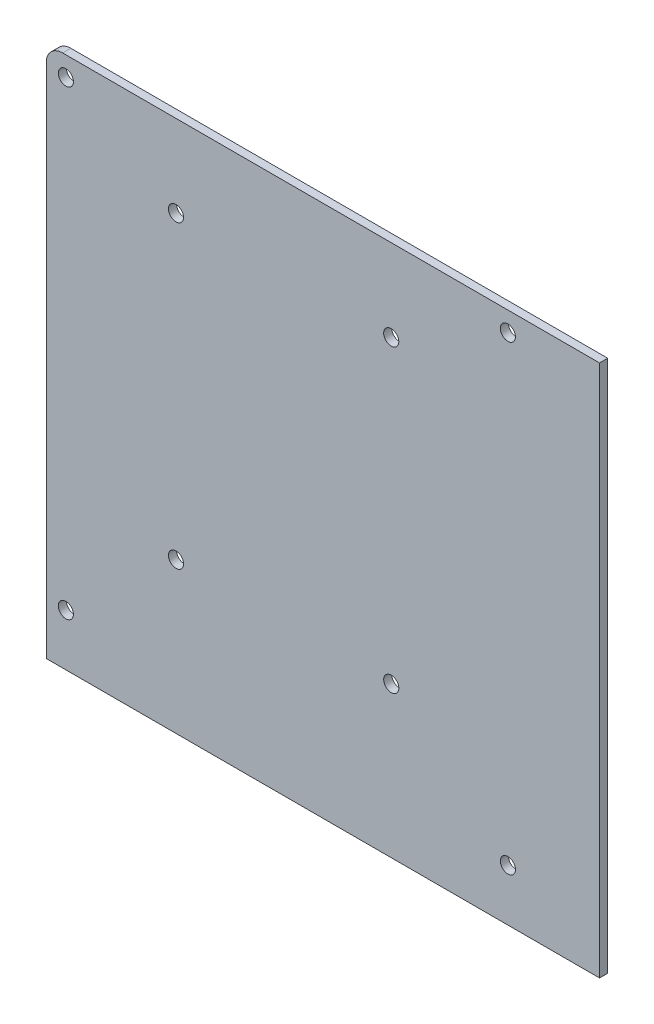
SolidWorks part; units mm, degrees
ref_plane "Front Plane" through (0, 0, 0) normal (0, 0, 1) x (1, 0, 0)
ref_plane "Top Plane" through (0, 0, 0) normal (0, 1, 0) x (1, 0, 0)
ref_plane "Right Plane" through (0, 0, 0) normal (1, 0, 0) x (0, 0, -1)
sketch "Sketch1" plane through (0, 0, 0) normal (0, 0, 1) x (1, 0, 0)
  line L1 (0, 0) -> (254, 0)
  line L2 (0, 0) -> (0, 381)
  line L3 (0, 381) -> (254, 381)
  line L4 (254, 0) -> (254, 381)
  dimension "D1" = 381
  dimension "D2" = 254
extrude "Boss-Extrude1" add sketch "Sketch1" along normal blind 1.5875
sketch "Sketch2" plane through (0, 0, 1.5875) normal (0, 0, 1) x (1, 0, 0)
  line L0 (89.8652, 377.19) -> (89.8652, 3.81) construction
  line L1 (0, 381) -> (254, 381) construction
  line L2 (127, 381) -> (127, 377.19) construction
  line L3 (3.81, 377.19) -> (250.19, 377.19) construction
  line L5 (164.1348, 377.19) -> (164.1348, 3.81) construction
  line L6 (3.81, 377.19) -> (3.81, 3.81) construction
  line L7 (3.81, 3.81) -> (250.19, 3.81) construction
  line L8 (250.19, 3.81) -> (250.19, 377.19) construction
  line L9 (3.81, 190.5) -> (250.19, 190.5) construction
  line L10 (3.81, 287.3756) -> (250.19, 287.3756) construction
  line L11 (3.81, 93.6244) -> (250.19, 93.6244) construction
  line L12 (0, 381) -> (0, 0) construction
  line L13 (0, 190.5) -> (3.81, 190.5) construction
  circle A0 centre (3.81, 377.19) radius 1.4732
  circle A1 centre (89.8652, 377.19) radius 1.4732
  circle A2 centre (164.1348, 377.19) radius 1.4732
  circle A3 centre (250.19, 377.19) radius 1.4732
  circle A4 centre (164.1348, 287.3755) radius 1.4732
  circle A5 centre (3.81, 287.3756) radius 1.4732
  circle A6 centre (250.19, 287.3756) radius 1.4732
  circle A7 centre (89.8652, 287.3756) radius 1.4732
  circle A8 centre (164.1348, 190.5) radius 1.4732
  circle A9 centre (3.81, 191.135) radius 1.4732
  circle A10 centre (250.19, 190.5) radius 1.4732
  circle A11 centre (89.8652, 190.5) radius 1.4732
  circle A12 centre (164.1348, 93.6244) radius 1.4732
  circle A13 centre (3.81, 93.6244) radius 1.4732
  circle A14 centre (250.19, 93.6244) radius 1.4732
  circle A15 centre (89.8652, 93.6244) radius 1.4732
  circle A16 centre (164.1348, 3.81) radius 1.4732
  circle A17 centre (3.81, 3.81) radius 1.4732
  circle A18 centre (250.19, 3.81) radius 1.4732
  circle A19 centre (89.8652, 3.81) radius 1.4732
  dimension "D6" = 2.9464
  dimension "D23" = 0
  dimension "D24" = 0
  dimension "D25" = 0
  dimension "D28" = 0
  dimension "D29" = 0
  dimension "D30" = 0
  dimension "D31" = 0
  dimension "D32" = 86.0552
  dimension "D1" = 246.38
  dimension "D3" = 373.38
  dimension "D4" = 96.8756
  dimension "D5" = 96.8756
  dimension "D7" = 86.0552
  dimension "D8" = 86.0552
  dimension "D9" = 0
  dimension "D10" = 0
  dimension "D11" = 0
  dimension "D12" = 86.0552
  dimension "D13" = 0
  dimension "D14" = 0
  dimension "D15" = 0
  dimension "D16" = 0
  dimension "D17" = 0
  dimension "D18" = 0
  dimension "D19" = 0
  dimension "D20" = 0
  dimension "D21" = 0
  dimension "D22" = 0
  dimension "D26" = 0
  dimension "D27" = 0
extrude "Cut-Extrude1" cut sketch "Sketch2" against normal through all contours A0 | A2 | A3
fillet "Fillet1" radius 3.175 4 edges at (254, 0, 0.7937) (0, 0, 0.7937) (254, 381, 0.7937) (0, 381, 0.7937)
sketch "Sketch3" plane through (0, 0, 1.5875) normal (0, 0, 1) x (1, 0, 0)
  line L0 (9.9695, 45.1866) -> (46.2026, 45.1866) construction
  line L1 (46.2026, 45.1866) -> (46.2026, 9.9695) construction
  line L2 (81.2038, 28.3591) -> (82.4357, 28.3591) construction
  line L3 (82.4357, 29.591) -> (82.4357, 60.7822)
  line L4 (73.0377, 11.2014) -> (73.0377, 20.193)
  line L5 (81.2038, 62.0141) -> (82.4357, 62.0141) construction
  line L6 (71.8058, 9.9695) -> (20.5994, 9.9695)
  line L7 (19.3675, 11.2014) -> (19.3675, 20.193)
  line L8 (11.2014, 28.3591) -> (9.9695, 28.3591) construction
  line L9 (9.9695, 29.591) -> (9.9695, 60.7822)
  line L10 (73.0377, 79.1718) -> (73.0377, 70.1802)
  line L11 (71.8058, 80.4037) -> (20.5994, 80.4037)
  line L12 (3.175, 0) -> (250.825, 0) construction
  line L13 (0, 377.825) -> (0, 3.175) construction
  line L14 (11.2014, 62.0141) -> (9.9695, 62.0141) construction
  line L15 (19.3675, 79.1718) -> (19.3675, 70.1802)
  line L16 (17.78, 79.1718) -> (17.78, 70.1802)
  line L17 (8.382, 29.591) -> (8.382, 60.7822)
  line L18 (17.78, 11.2014) -> (17.78, 20.193)
  line L19 (71.8058, 8.382) -> (20.5994, 8.382)
  line L20 (74.6252, 11.2014) -> (74.6252, 20.193)
  line L21 (84.0232, 29.591) -> (84.0232, 60.7822)
  line L22 (74.6252, 79.1718) -> (74.6252, 70.1802)
  line L23 (71.8058, 81.9912) -> (20.5994, 81.9912)
  arc A0 (19.3675, 20.193) -> (11.2014, 28.3591) centre (11.2014, 20.193) ccw
  arc A1 (9.9695, 29.591) -> (11.2014, 28.3591) centre (11.2014, 29.591) ccw
  arc A2 (19.3675, 11.2014) -> (20.5994, 9.9695) centre (20.5994, 11.2014) ccw
  arc A3 (73.0377, 11.2014) -> (71.8058, 9.9695) centre (71.8058, 11.2014) cw
  arc A4 (82.4357, 29.591) -> (81.2038, 28.3591) centre (81.2038, 29.591) cw
  arc A5 (73.0377, 20.193) -> (81.2038, 28.3591) centre (81.2038, 20.193) cw
  arc A6 (73.0377, 70.1802) -> (81.2038, 62.0141) centre (81.2038, 70.1802) ccw
  arc A7 (82.4357, 60.7822) -> (81.2038, 62.0141) centre (81.2038, 60.7822) ccw
  arc A8 (73.0377, 79.1718) -> (71.8058, 80.4037) centre (71.8058, 79.1718) ccw
  arc A9 (19.3675, 79.1718) -> (20.5994, 80.4037) centre (20.5994, 79.1718) cw
  arc A10 (9.9695, 60.7822) -> (11.2014, 62.0141) centre (11.2014, 60.7822) cw
  arc A11 (19.3675, 70.1802) -> (11.2014, 62.0141) centre (11.2014, 70.1802) cw
  arc A12 (17.78, 70.1802) -> (11.2014, 63.6016) centre (11.2014, 70.1802) cw
  arc A13 (8.382, 60.7822) -> (11.2014, 63.6016) centre (11.2014, 60.7822) cw
  arc A14 (8.382, 29.591) -> (11.2014, 26.7716) centre (11.2014, 29.591) ccw
  arc A15 (17.78, 20.193) -> (11.2014, 26.7716) centre (11.2014, 20.193) ccw
  arc A16 (17.78, 11.2014) -> (20.5994, 8.382) centre (20.5994, 11.2014) ccw
  arc A17 (74.6252, 11.2014) -> (71.8058, 8.382) centre (71.8058, 11.2014) cw
  arc A18 (74.6252, 20.193) -> (81.2038, 26.7716) centre (81.2038, 20.193) cw
  arc A19 (84.0232, 29.591) -> (81.2038, 26.7716) centre (81.2038, 29.591) cw
  arc A20 (84.0232, 60.7822) -> (81.2038, 63.6016) centre (81.2038, 60.7822) ccw
  arc A21 (74.6252, 70.1802) -> (81.2038, 63.6016) centre (81.2038, 70.1802) ccw
  arc A22 (74.6252, 79.1718) -> (71.8058, 81.9912) centre (71.8058, 79.1718) ccw
  arc A23 (17.78, 79.1718) -> (20.5994, 81.9912) centre (20.5994, 79.1718) cw
  point P35 (82.4357, 45.1866)
  dimension "D6" = 8.1661
  dimension "D7" = 2.4638
  dimension "D8" = 1.2319
  dimension "D1" = 9.9695
  dimension "D2" = 9.9695
  dimension "D3" = 19.3675
  dimension "D4" = 28.3591
  dimension "D5" = 45.1866
  dimension "D10" = 46.2026
  dimension "D9" = 1.5875
sketch "Sketch4" plane through (0, 0, 1.5875) normal (0, 0, 1) x (1, 0, 0)
  line L0 (8.382, 60.7822) -> (8.382, 77.2287)
  line L1 (13.1445, 81.9912) -> (20.5994, 81.9912)
  line L2 (20.5994, 81.9912) -> (79.2607, 81.9912)
  line L3 (84.0232, 77.2287) -> (84.0232, 13.1445)
  line L4 (79.2607, 8.382) -> (13.1445, 8.382)
  line L5 (8.382, 13.1445) -> (8.382, 60.7822)
  line L6 (6.477, 60.7822) -> (6.477, 77.2287)
  line L7 (13.1445, 83.8962) -> (20.5994, 83.8962)
  line L8 (20.5994, 83.8962) -> (79.2607, 83.8962)
  line L9 (85.9282, 77.2287) -> (85.9282, 13.1445)
  line L10 (79.2607, 6.477) -> (13.1445, 6.477)
  line L11 (6.477, 13.1445) -> (6.477, 60.7822)
  arc A0 (13.1445, 81.9912) -> (8.382, 77.2287) centre (13.1445, 77.2287) ccw
  arc A1 (79.2607, 81.9912) -> (84.0232, 77.2287) centre (79.2607, 77.2287) cw
  arc A2 (84.0232, 13.1445) -> (79.2607, 8.382) centre (79.2607, 13.1445) cw
  arc A3 (8.382, 13.1445) -> (13.1445, 8.382) centre (13.1445, 13.1445) ccw
  arc A4 (13.1445, 83.8962) -> (6.477, 77.2287) centre (13.1445, 77.2287) ccw
  arc A5 (79.2607, 83.8962) -> (85.9282, 77.2287) centre (79.2607, 77.2287) cw
  arc A6 (85.9282, 13.1445) -> (79.2607, 6.477) centre (79.2607, 13.1445) cw
  arc A7 (6.477, 13.1445) -> (13.1445, 6.477) centre (13.1445, 13.1445) ccw
  dimension "D1" = 4.7625
  dimension "D2" = 1.905
sketch "Sketch5" plane through (0, 0, 1.5875) normal (0, 0, 1) x (1, 0, 0)
  line L0 (9.9695, 45.1866) -> (82.4357, 45.1866) construction
  line L1 (9.9695, 60.7822) -> (9.9695, 29.591) construction
  line L2 (82.4357, 29.591) -> (82.4357, 60.7822) construction
  line L3 (82.4357, 45.1866) -> (46.2026, 45.1866) construction
  line L4 (46.2026, 45.1866) -> (46.2026, 80.4037) construction
  line L5 (71.8058, 80.4037) -> (20.5994, 80.4037) construction
  circle A0 centre (25.2476, 74.3966) radius 1.4732
  circle A1 centre (67.1576, 74.3966) radius 1.4732
  circle A2 centre (67.1576, 15.9766) radius 1.4732
  circle A3 centre (25.2476, 15.9766) radius 1.4732
  dimension "D1" = 2.9464
  dimension "D2" = 20.955
  dimension "D3" = 29.21
extrude "Cut-Extrude3" cut sketch "Sketch5" against normal through all
pattern_linear "LPattern1" count 4 spacing 96.8756 along (0, 1, 0) count 2 spacing 161.5948 along (1, 0, 0) of "Cut-Extrude3"
sketch "Sketch6" plane through (0, 0, 1.5875) normal (0, 0, 1) x (1, 0, 0)
  line L1 (0, 381) -> (107.7145, 381)
  line L2 (0, 381) -> (0, 277.295)
  line L3 (0, 277.295) -> (107.7145, 277.295)
  line L4 (107.7145, 381) -> (107.7145, 277.295)
  line L5 (0, 381) -> (295.5521, 381)
  line L6 (0, 381) -> (0, -37.8947)
  line L7 (0, -37.8947) -> (295.5521, -37.8947)
  line L8 (295.5521, 381) -> (295.5521, -37.8947)
extrude "Cut-Extrude4" cut sketch "Sketch6" against normal through all contours L8 L5 L4 L3 L6 L7
